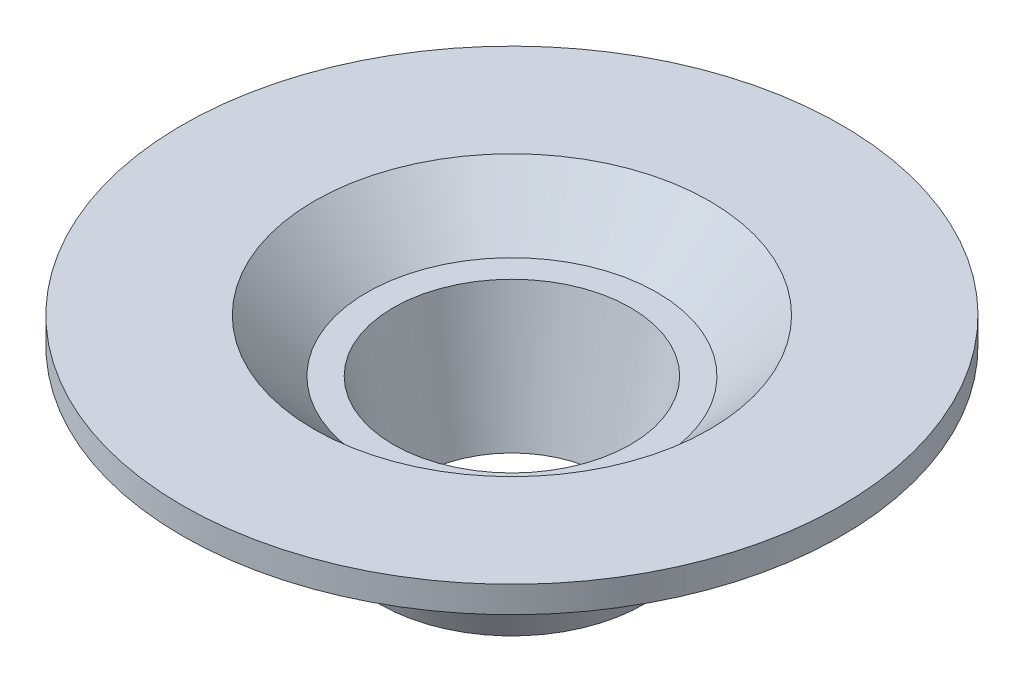
SolidWorks part; units mm, degrees
ref_plane "Front Plane" through (0, 0, 0) normal (0, 0, 1) x (1, 0, 0)
ref_plane "Top Plane" through (0, 0, 0) normal (0, 1, 0) x (1, 0, 0)
ref_plane "Right Plane" through (0, 0, 0) normal (1, 0, 0) x (0, 0, -1)
sketch "Sketch1" plane through (0, 0, 0) normal (1, 0, 0) x (0, 0, -1)
  line L0 (0, 0) -> (0, -5) construction
  line L1 (3.5, -5) -> (4.5, 0)
  line L2 (4.5, 0) -> (5.5, 0)
  line L3 (5.5, 0) -> (7.5, 2)
  line L4 (7.5, 2) -> (12.5, 2)
  line L5 (12.5, 2) -> (12.5, 1)
  line L6 (12.5, 1) -> (10.5, 1)
  line L7 (10.5, 1) -> (8.5, -1)
  line L8 (8.5, -1) -> (6.5, -1)
  line L9 (6.5, -1) -> (5, -5)
  line L10 (5, -5) -> (3.5, -5)
  point P6 (0, 0)
  point P16 (7.2494, 1.7002)
  dimension "D1" = 5
  dimension "D2" = 1.5
  dimension "D3" = 3.5
  dimension "D4" = 4.5
  dimension "D5" = 4
  dimension "D6" = 2
  dimension "D7" = 2
  dimension "D8" = 12.5
  dimension "D9" = 1
  dimension "D10" = 2
  dimension "D11" = 1
  dimension "D12" = 6.5
  dimension "D13" = 9.246
revolve "Revolve1" add sketch "Sketch1" angle 360 about L0
